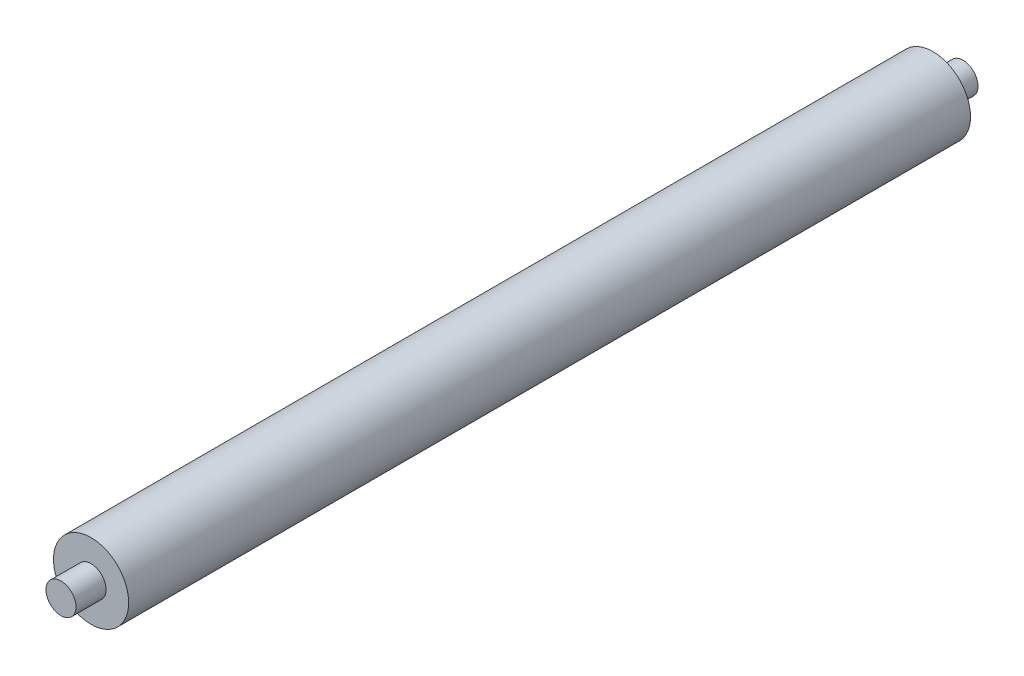
SolidWorks part; units mm, degrees
ref_plane "Front Plane" through (0, 0, 0) normal (0, 0, 1) x (1, 0, 0)
ref_plane "Top Plane" through (0, 0, 0) normal (0, 1, 0) x (1, 0, 0)
ref_plane "Right Plane" through (0, 0, 0) normal (1, 0, 0) x (0, 0, -1)
sketch "Sketch1" plane through (0, 0, 0) normal (0, 0, 1) x (1, 0, 0)
  circle A0 centre (0, 0) radius 12.5
  dimension "D1" = 25
extrude "Boss-Extrude1" add sketch "Sketch1" along normal blind 280
sketch "Sketch2" plane through (0, 0, 280) normal (0, 0, 1) x (1, 0, 0)
  circle A0 centre (0, 0) radius 5
  dimension "D1" = 10
extrude "Boss-Extrude2" add sketch "Sketch2" along normal blind 10
sketch "Sketch3" plane through (0, 0, 0) normal (0, 0, -1) x (-1, 0, 0)
  circle A0 centre (0, 0) radius 5
  dimension "D1" = 10
extrude "Boss-Extrude3" add sketch "Sketch3" along normal blind 10
